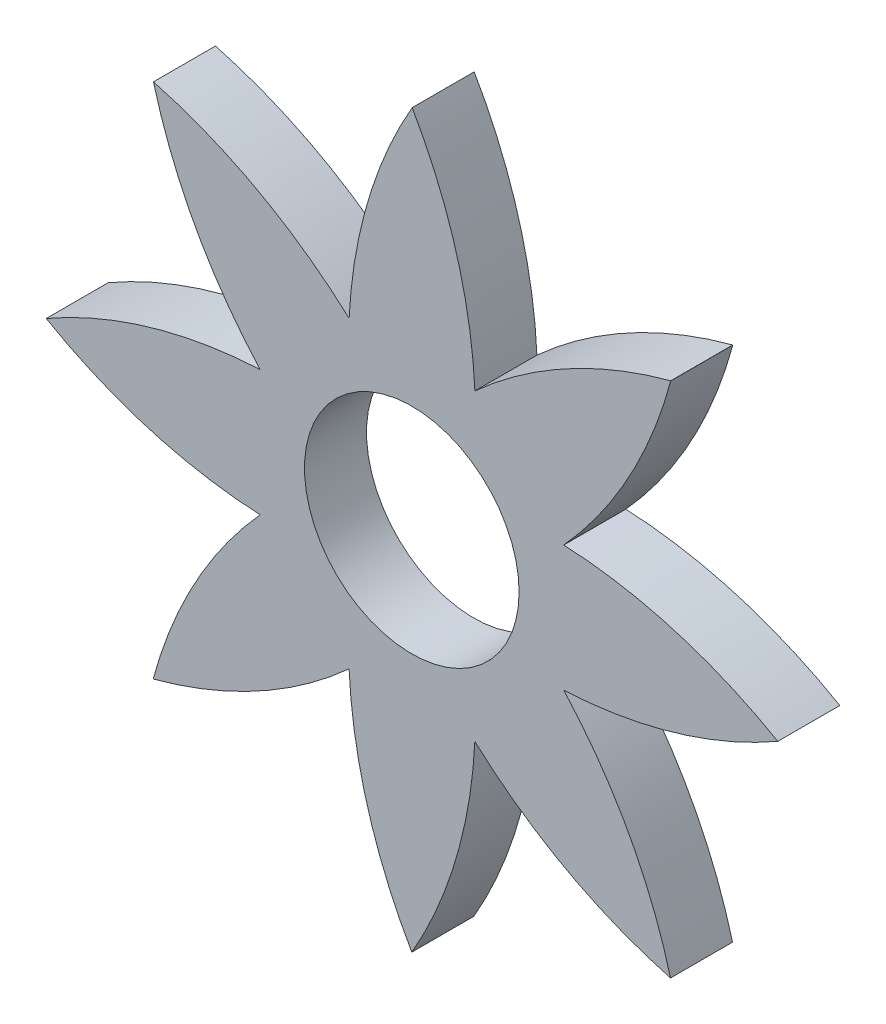
SolidWorks part; units mm, degrees
ref_plane "Front Plane" through (0, 0, 0) normal (0, 0, 1) x (1, 0, 0)
ref_plane "Top Plane" through (0, 0, 0) normal (0, 1, 0) x (1, 0, 0)
ref_plane "Right Plane" through (0, 0, 0) normal (1, 0, 0) x (0, 0, -1)
sketch "Sketch1" plane through (0, 0, 0) normal (0, 0, 1) x (1, 0, 0)
  line L1 (-50.8, -50.8) -> (50.8, -50.8)
  line L2 (-50.8, -50.8) -> (-50.8, 50.8)
  line L3 (-50.8, 50.8) -> (50.8, 50.8)
  line L4 (50.8, -50.8) -> (50.8, 50.8)
  line L5 (-50.8, -50.8) -> (50.8, 50.8) construction
  line L6 (-50.8, 50.8) -> (50.8, -50.8) construction
  circle A0 centre (0, 0) radius 37.465
  circle A1 centre (0, 0) radius 10.9855
  circle A2 centre (0, 0) radius 4.0386
  arc A3 (15.5603, 6.4536) -> (37.465, 0) centre (13.1837, -42.0144) cw
  arc A4 (15.5579, -6.4194) -> (37.465, 0) centre (13.2485, 42.0518) ccw
  arc A5 (15.5579, -6.4194) -> (26.4835, -26.4718) centre (-20.3946, -39.0109) cw
  arc A6 (6.4536, -15.5203) -> (26.4835, -26.4718) centre (39.0949, 20.387) ccw
  arc A7 (6.4536, -15.5203) -> (0, -37.4251) centre (-42.0144, -13.1437) cw
  arc A8 (-6.4194, -15.5179) -> (0, -37.4251) centre (42.0518, -13.2085) ccw
  arc A9 (-6.4194, -15.5179) -> (-26.4718, -26.4435) centre (-39.0109, 20.4346) cw
  arc A10 (-15.5203, -6.4136) -> (-26.4718, -26.4435) centre (20.387, -39.055) ccw
  arc A11 (-15.5203, -6.4136) -> (-37.425, 0.0399) centre (-13.1437, 42.0543) cw
  arc A12 (-15.5179, 6.4594) -> (-37.425, 0.0399) centre (-13.2085, -42.0118) ccw
  arc A13 (-15.5179, 6.4594) -> (-26.4435, 26.5117) centre (20.4346, 39.0509) cw
  arc A14 (-6.4136, 15.5603) -> (-26.4435, 26.5117) centre (-39.0549, -20.3471) ccw
  arc A15 (-6.4136, 15.5603) -> (0.0399, 37.465) centre (42.0543, 13.1837) cw
  arc A16 (6.4594, 15.5579) -> (0.0399, 37.465) centre (-42.0118, 13.2484) ccw
  arc A17 (6.4594, 15.5579) -> (26.5117, 26.4835) centre (39.0509, -20.3947) cw
  arc A18 (15.5603, 6.4536) -> (26.5117, 26.4835) centre (-20.347, 39.0949) ccw
  arc A19 (4.1873, 11.9899) -> (-3.7224, 12.1422) centre (0, 0) ccw construction
  spline S0 degree 2 poles (24.6495, 24.6495) (25.541, 24.6368) (26.1135, 25.0873) knots 0 0 0 0.598691 0.598691 0.598691
  spline S1 degree 2 poles (24.6495, 24.6495) (24.6373, 25.5066) (25.0533, 26.0688) knots 0 0 0 0.575594 0.575594 0.575594
  spline S2 degree 2 poles (34.8596, 0) (35.4709, -0.6204) (36.1943, -0.7066) knots 0 0 0 0.598691 0.598691 0.598691
  spline S3 degree 2 poles (34.8596, 0) (35.4636, 0.6267) (36.1553, 0.7302) knots 0 0 0 0.575594 0.575594 0.575594
  spline S4 degree 2 poles (24.6495, -24.6495) (24.6478, -25.5043) (25.0984, -26.0769) knots 0 0 0 0.598691 0.598691 0.598691
  spline S5 degree 2 poles (24.6495, -24.6495) (25.5176, -24.634) (26.0799, -25.0499) knots 0 0 0 0.575594 0.575594 0.575594
  spline S6 degree 2 poles (0, -34.8596) (-0.6393, -35.481) (-0.7256, -36.2044) knots 0 0 0 0.598691 0.598691 0.598691
  spline S7 degree 2 poles (0, -34.8596) (0.6147, -35.4571) (0.7181, -36.1488) knots 0 0 0 0.575594 0.575594 0.575594
  spline S8 degree 2 poles (-24.6495, -24.6495) (-25.541, -24.6368) (-26.1135, -25.0873) knots 0 0 0 0.598691 0.598691 0.598691
  spline S9 degree 2 poles (-24.6495, -24.6495) (-24.6373, -25.5066) (-25.0533, -26.0688) knots 0 0 0 0.575594 0.575594 0.575594
  spline S10 degree 2 poles (-34.8596, 0) (-35.481, 0.6393) (-36.2044, 0.7256) knots 0 0 0 0.598691 0.598691 0.598691
  spline S11 degree 2 poles (-34.8596, 0) (-35.4571, -0.6147) (-36.1488, -0.7181) knots 0 0 0 0.575594 0.575594 0.575594
  spline S12 degree 2 poles (-24.6495, 24.6495) (-24.6335, 25.552) (-25.084, 26.1245) knots 0 0 0 0.598691 0.598691 0.598691
  spline S13 degree 2 poles (-24.6495, 24.6495) (-25.5066, 24.6373) (-26.0688, 25.0533) knots 0 0 0 0.575594 0.575594 0.575594
  spline S14 degree 2 poles (0, 34.8596) (0.6393, 35.5099) (0.7256, 36.2333) knots 0 0 0 0.598691 0.598691 0.598691
  spline S15 degree 2 poles (0, 34.8596) (-0.5803, 35.4756) (-0.6837, 36.1673) knots 0 0 0 0.575594 0.575594 0.575594
  text T0 "Paulina" font "Century Schoolbook" height 1.524
  point P0 (0, 0)
  point P53 (0.02, 0.02)
  point P69 (0, 0)
  point P70 (0, 0)
  point P72 (0, 0)
  point P73 (0, 0)
  point P74 (0, 0)
  point P75 (0, 0)
  point P76 (0, 0)
  point P77 (0, 0)
  point P78 (0, 0)
  point P79 (0, 0)
  point P80 (0, 0)
  dimension "D3" = 74.93
  dimension "D4" = 21.971
  dimension "D5" = 8.0772
  dimension "D9" = 16.8086
  dimension "D11" = 48.5262
  dimension "D14" = 1.5281
  dimension "D15" = 2.6056
  dimension "D22" = 12.7
  dimension "D1" = 101.6
  dimension "D2" = 101.6
  dimension "D7" = 37.465
  dimension "D8" = 12.873
  dimension "D10" = 35.6732
  dimension "D12" = 1.4757
  dimension "D13" = 2.6137
  dimension "D16" = 1.4757
  dimension "D17" = 0.7256
  dimension "D18" = 1.8223
  dimension "D19" = 1.4448
  dimension "D20" = 0.4378
  dimension "D21" = 1.4757
  dimension "D6" = 8
extrude "Boss-Extrude2" add sketch "Sketch1" along normal blind 6.35 contours S14 S15 A15 A14 S12 S13 A13 A12 S10 S11 A11 A10 S8 S9 A9 A8 S6 S7 A7 A6 S4 S5 A5 A4 S2 S3 A3 A18 S0 S1 A17 A16 A1 | S15 S14 A16 A15 | S13 S12 A14 A13 | S11 S10 A12 A11 | S9 S8 A10 A9 | S7 S6 A8 A7 | S5 S4 A6 A5 | S3 S2 A4 A3 | S1 S0 A18 A0 A17
